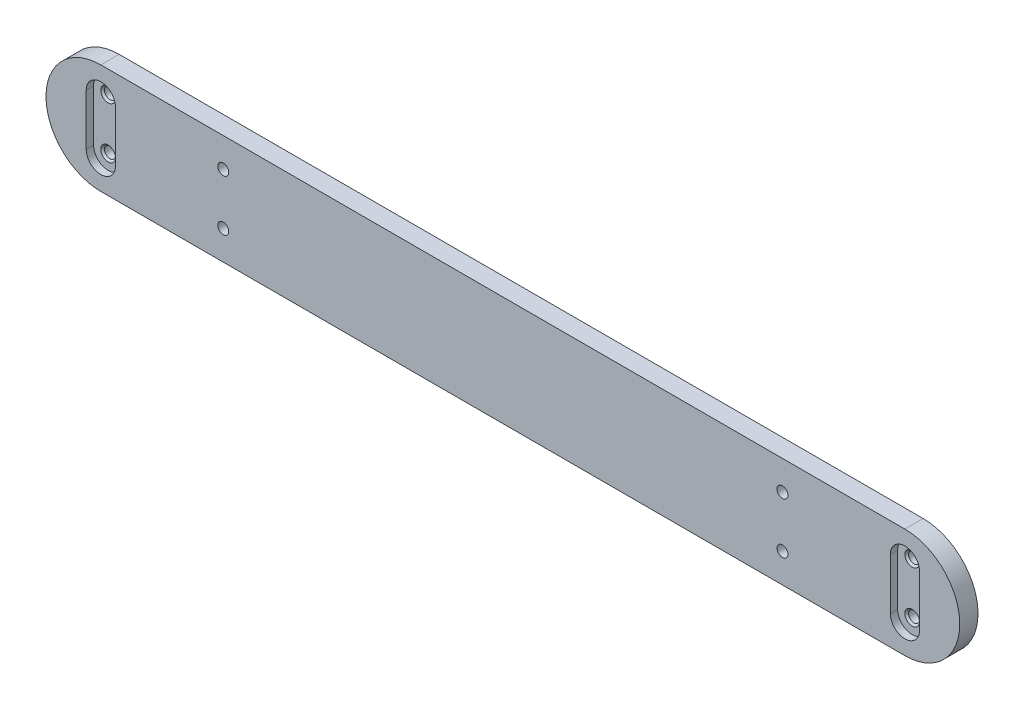
SolidWorks part; units mm, degrees
ref_plane "前视基准面" through (0, 0, 0) normal (0, 0, 1) x (1, 0, 0)
ref_plane "上视基准面" through (0, 0, 0) normal (0, 1, 0) x (1, 0, 0)
ref_plane "右视基准面" through (0, 0, 0) normal (1, 0, 0) x (0, 0, -1)
sketch "草图1" plane through (0, 0, 0) normal (0, 0, 1) x (1, 0, 0)
  line L0 (-110, 0) -> (110, 0) construction
  line L1 (-110, 15) -> (110, 15)
  line L2 (-110, -15) -> (110, -15)
  arc A0 (-110, 15) -> (-110, -15) centre (-110, 0) ccw
  arc A1 (110, -15) -> (110, 15) centre (110, 0) ccw
  point P3 (0, 0)
  dimension "D2" = 15
  dimension "D1" = 220
  dimension "D3" = 110
extrude "凸台-拉伸1" add sketch "草图1" along normal blind 5
sketch "草图2" plane through (0, 0, 5) normal (0, 0, 1) x (1, 0, 0)
  line L0 (110, 7) -> (110, -7) construction
  line L1 (114, 7) -> (114, -7)
  line L2 (106, 7) -> (106, -7)
  line L3 (-110, 7) -> (-110, -7) construction
  line L4 (-106, 7) -> (-106, -7)
  line L5 (-114, 7) -> (-114, -7)
  arc A2 (114, 7) -> (106, 7) centre (110, 7) ccw
  arc A3 (106, -7) -> (114, -7) centre (110, -7) ccw
  arc A4 (-106, 7) -> (-114, 7) centre (-110, 7) ccw
  arc A5 (-114, -7) -> (-106, -7) centre (-110, -7) ccw
  point P4 (110, 0)
  point P10 (-110, 0)
  dimension "D1" = 110
  dimension "D2" = 4
  dimension "D6" = 4
  dimension "D3" = 14
  dimension "D5" = 110
  dimension "D7" = 14
extrude "切除-拉伸1" cut sketch "草图2" against normal blind 2
sketch "草图4" plane through (0, 0, 0) normal (0, 0, -1) x (-1, 0, 0)
  line L0 (-76.5, 7.5) -> (-76.5, -7.5) construction
  line L1 (-71.5, 7.5) -> (-71.5, -7.5)
  line L2 (-81.5, 7.5) -> (-81.5, -7.5)
  line L3 (0, 0) -> (0, -50000) construction
  line L4 (76.5, 7.5) -> (76.5, -7.5) construction
  line L5 (71.5, 7.5) -> (71.5, -7.5)
  line L6 (81.5, 7.5) -> (81.5, -7.5)
  arc A0 (-71.5, 7.5) -> (-81.5, 7.5) centre (-76.5, 7.5) ccw
  arc A1 (-81.5, -7.5) -> (-71.5, -7.5) centre (-76.5, -7.5) ccw
  arc A2 (71.5, 7.5) -> (81.5, 7.5) centre (76.5, 7.5) cw
  arc A3 (81.5, -7.5) -> (71.5, -7.5) centre (76.5, -7.5) cw
  point P2 (-76.5, 0)
  point P12 (76.5, 0)
  dimension "D2" = 5
  dimension "D1" = 76.5
  dimension "D3" = 15
extrude "切除-拉伸2" cut sketch "草图4" against normal blind 2
sketch "草图6" plane through (0, 0, 2) normal (0, 0, -1) x (-1, 0, 0)
  line L0 (0, 0) -> (50000, 0) construction
  line L1 (0, 0) -> (0, 50000) construction
  circle A0 centre (76.5, 7) radius 1.5
  circle A1 centre (76.5, -7) radius 1.5
  circle A2 centre (-76.5, 7) radius 1.5
  circle A3 centre (-76.5, -7) radius 1.5
  dimension "D1" = 3
  dimension "D2" = 7
  dimension "D3" = 76.5
extrude "切除-拉伸4" cut sketch "草图6" against normal through all and the other way through all
sketch "草图7" plane through (0, 0, 3) normal (0, 0, 1) x (1, 0, 0)
  circle A0 centre (110, 7) radius 1.5
  circle A1 centre (110, -7) radius 1.5
  circle A2 centre (-110, 7) radius 1.5
  circle A3 centre (-110, -7) radius 1.5
  dimension "D1" = 3
  dimension "D2" = 3
  dimension "D3" = 3
  dimension "D4" = 3
extrude "切除-拉伸5" cut sketch "草图7" against normal through all
chamfer "倒角1" distance 0.5 angle 45 4 edges at (-108.5, -7, 3) (-108.5, 7, 3) (111.5, -7, 3) (111.5, 7, 3)
chamfer "倒角2" distance 0.5 angle 45 4 edges at (75, 7, 2) (75, -7, 2) (-75, -7, 2) (-75, 7, 2)
